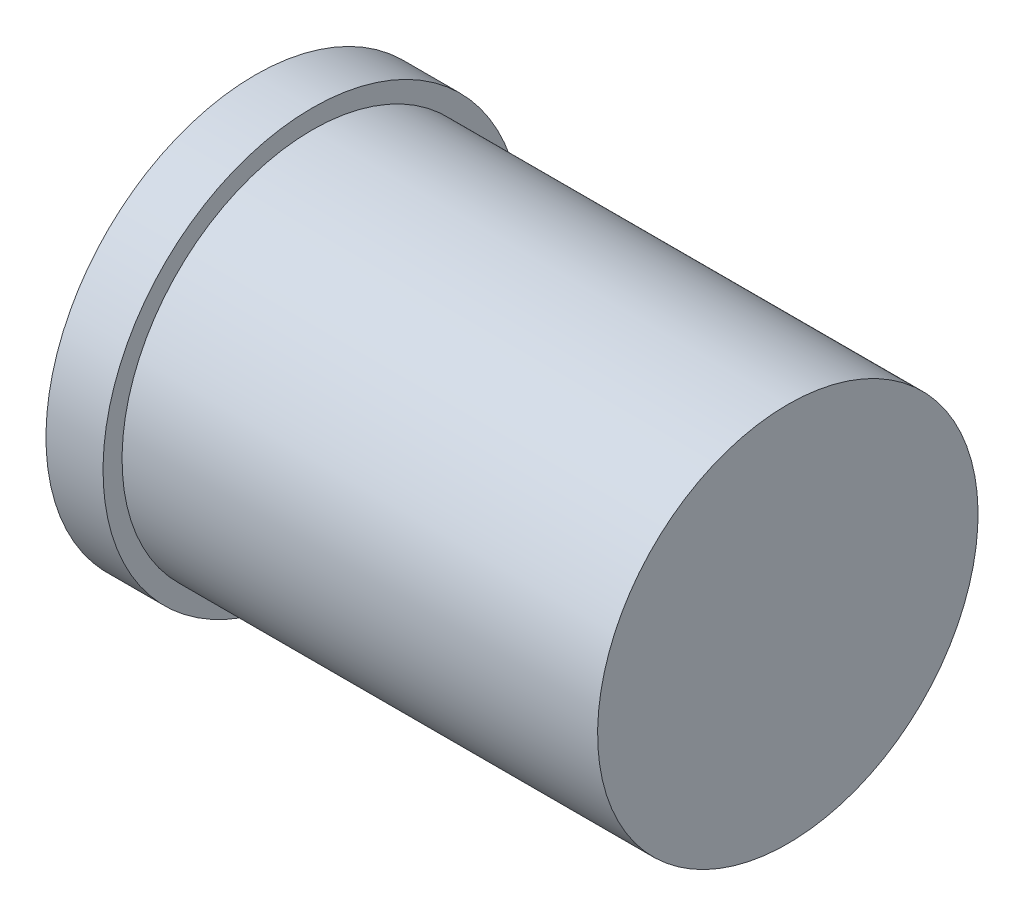
SolidWorks part; units mm, degrees
ref_plane "Front Plane" through (0, 0, 0) normal (0, 0, 1) x (1, 0, 0)
ref_plane "Top Plane" through (0, 0, 0) normal (0, 1, 0) x (1, 0, 0)
ref_plane "Right Plane" through (0, 0, 0) normal (1, 0, 0) x (0, 0, -1)
sketch "Sketch1" plane through (0, 0, 0) normal (0, 0, 1) x (1, 0, 0)
  line L0 (0, 0) -> (0, 11)
  line L1 (0, 11) -> (3, 11)
  line L2 (3, 11) -> (3, 10)
  line L3 (3, 10) -> (28, 10)
  line L4 (28, 10) -> (28, 0)
  line L5 (28, 0) -> (0, 0)
  dimension "D1" = 3
  dimension "D2" = 10
  dimension "D3" = 11
  dimension "D4" = 25
revolve "Revolve1" add sketch "Sketch1" angle 360 about L5
